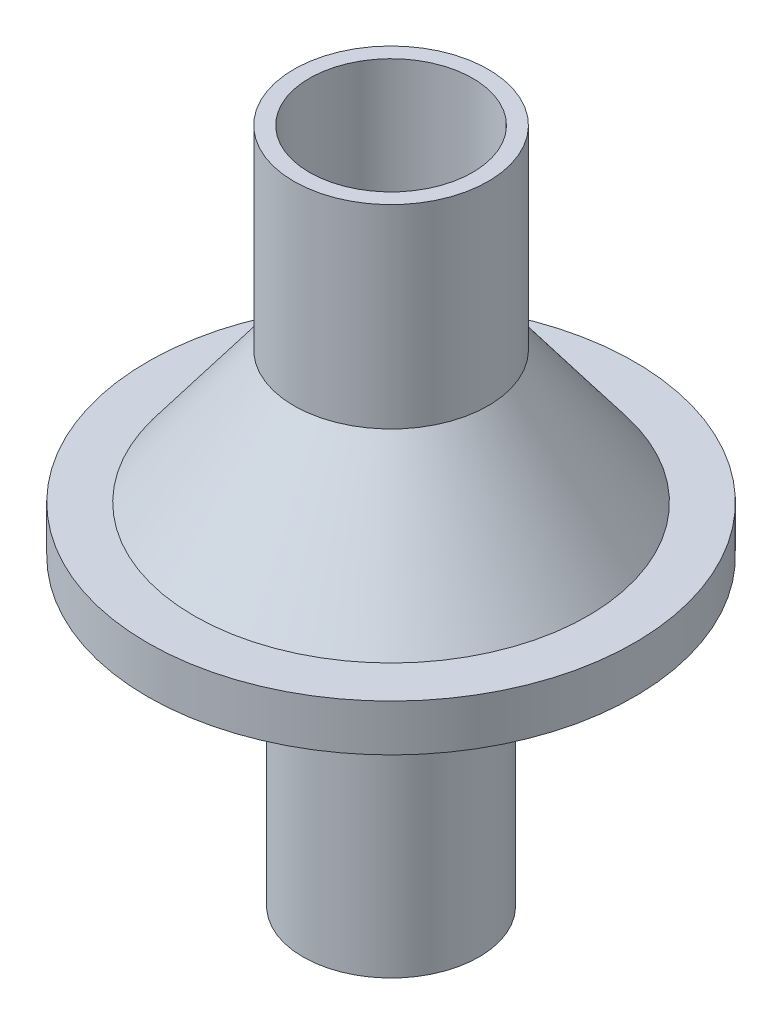
SolidWorks part; units mm, degrees
material "PVC Rigid"
ref_plane "Front" through (0, 0, 0) normal (0, 0, 1) x (1, 0, 0)
ref_plane "Top" through (0, 0, 0) normal (0, 1, 0) x (1, 0, 0)
ref_plane "Right" through (0, 0, 0) normal (1, 0, 0) x (0, 0, -1)
sketch "Sketch1" plane through (0, 0, 0) normal (0, 1, 0) x (1, 0, 0)
  circle A0 centre (0, 0) radius 11.325
  circle A1 centre (0, 0) radius 9.325
  dimension "D1" = 22.65
  dimension "D2" = 2
extrude "Boss-Extrude1" add sketch "Sketch1" along normal blind 25
sketch "Sketch6" plane through (0, 25, 0) normal (0, 1, 0) x (1, 0, 0)
  circle A1 centre (0, 0) radius 11.325
  circle A2 centre (0, 0) radius 11.325
  dimension "D1" = 0
sketch "Sketch9" plane through (0, 0, 0) normal (0, -1, 0) x (1, 0, 0)
  circle A0 centre (0, 0) radius 9.325 construction
  circle A1 centre (0, 0) radius 9.325
sketch "Sketch10" plane through (0, 0, 0) normal (0, 0, 1) x (1, 0, 0)
  line L0 (-11.325, 25) -> (-25.325, 39)
  line L1 (-25.325, 39) -> (-31.325, 39)
  line L2 (-31.325, 39) -> (-31.325, 42)
  line L3 (-31.325, 42) -> (-25.325, 42)
  line L4 (11.325, 25) -> (-11.325, 25) construction
  line L5 (-11.325, 25) -> (11.325, 25)
  line L6 (-25.325, 42) -> (-9.325, 25)
  line L7 (-11.325, 25) -> (11.325, 25) construction
  line L8 (11.325, 25) -> (11.325, 0)
  line L9 (11.325, 25) -> (11.325, 0) construction
  line L10 (11.325, 0) -> (-11.325, 0)
  line L11 (11.325, 0) -> (-11.325, 0) construction
  line L12 (-11.325, 0) -> (-11.325, 25)
  line L13 (-11.325, 0) -> (-11.325, 25) construction
  line L14 (-11.325, 25) -> (-9.325, 25)
  dimension "D1" = 6
  dimension "D2" = 3
  dimension "D3" = 17
  dimension "D4" = 20
ref_axis "Axis1" through (0, 25, 0) along (0, -1, 0)
revolve "Revolve1" add sketch "Sketch10" angle 360 about axis through (0, 25, 0) along (0, -1, 0)
sketch "Sketch11" plane through (0, 0, 0) normal (0, 0, 1) x (1, 0, 0)
  line L0 (11.325, 25) -> (11.325, 0)
  line L1 (11.325, 25) -> (11.325, 0) construction
  line L2 (11.325, 0) -> (-11.325, 0)
  line L3 (11.325, 0) -> (-11.325, 0) construction
  line L4 (-11.325, 0) -> (-11.325, 25)
  line L5 (-11.325, 0) -> (-11.325, 25) construction
  line L6 (-11.325, 25) -> (-25.325, 39)
  line L7 (-11.325, 25) -> (-25.325, 39) construction
  line L8 (-25.325, 39) -> (-31.325, 39)
  line L9 (-25.325, 39) -> (-31.325, 39) construction
  line L10 (-31.325, 39) -> (-31.325, 42)
  line L11 (-31.325, 39) -> (-31.325, 42) construction
  line L12 (-31.325, 42) -> (31.325, 42)
  line L13 (-31.325, 42) -> (31.325, 42) construction
  line L14 (31.325, 42) -> (31.325, 39)
  line L15 (31.325, 42) -> (31.325, 39) construction
  line L16 (31.325, 39) -> (25.325, 39)
  line L17 (31.325, 39) -> (25.325, 39) construction
  line L18 (25.325, 39) -> (11.325, 25)
  line L19 (25.325, 39) -> (11.325, 25) construction
  line L20 (-31.325, 42) -> (-31.325, 45)
  line L21 (-31.325, 45) -> (-25.325, 45)
  line L22 (-25.325, 45) -> (-12.5, 62)
  line L23 (-12.5, 62) -> (-12.5, 87)
  line L24 (-12.5, 87) -> (-10.5, 87)
  line L25 (-10.5, 87) -> (-10.5, 62)
  line L26 (-10.5, 62) -> (-25.325, 42)
  line L27 (-25.325, 42) -> (-31.325, 42)
  point P16 (0, 0)
  dimension "D1" = 3
  dimension "D2" = 2
  dimension "D3" = 6
  dimension "D4" = 17
  dimension "D5" = 12.5
  dimension "D6" = 6
  dimension "D7" = 25
revolve "Revolve2" add sketch "Sketch11" angle 360 about axis through (0, 25, 0) along (0, -1, 0)
